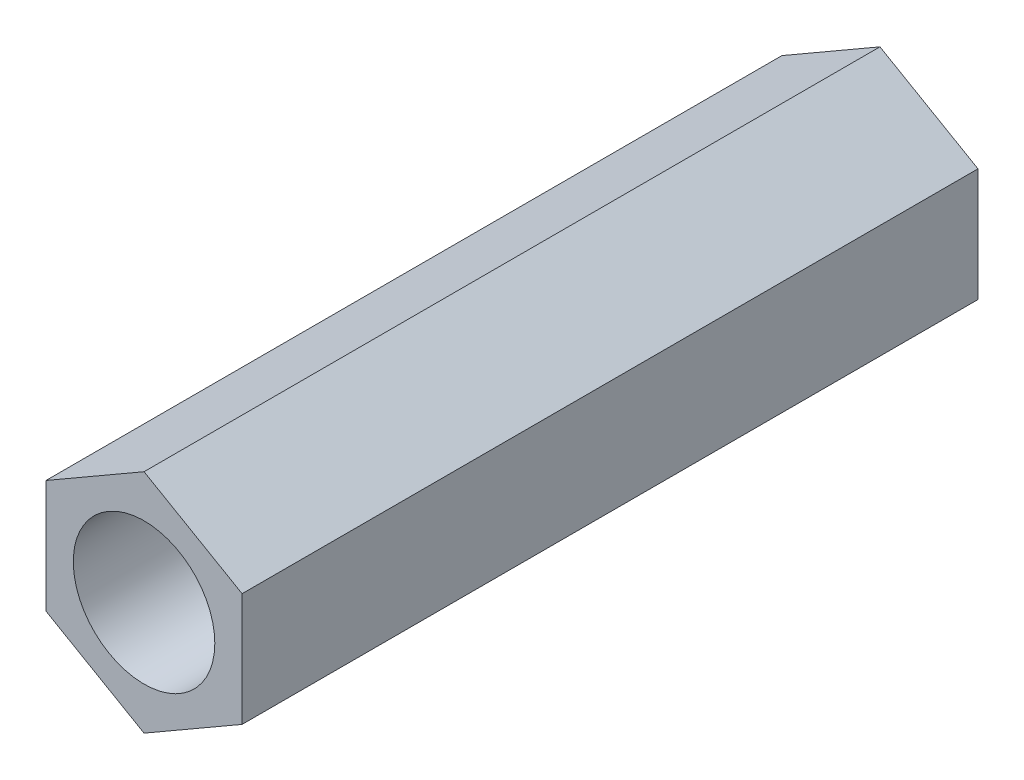
SolidWorks part; units mm, degrees
ref_plane "Front Plane" through (0, 0, 0) normal (0, 0, 1) x (1, 0, 0)
ref_plane "Top Plane" through (0, 0, 0) normal (0, 1, 0) x (1, 0, 0)
ref_plane "Right Plane" through (0, 0, 0) normal (1, 0, 0) x (0, 0, -1)
sketch "Sketch1" plane through (0, 0, 0) normal (0, 0, 1) x (1, 0, 0)
  line L0 (0, 108.4376) -> (0, -121.4916) construction
  line L1 (-136.8551, 0) -> (144.4002, 0) construction
  line L2 (0, 101.6) -> (87.9882, 50.8)
  line L3 (87.9882, 50.8) -> (87.9882, -50.8)
  line L4 (87.9882, -50.8) -> (0, -101.6)
  line L6 (-87.9882, -50.8) -> (0, -101.6)
  line L7 (-87.9882, 50.8) -> (-87.9882, -50.8)
  line L8 (0, 101.6) -> (-87.9882, 50.8)
  circle A1 centre (0, 0) radius 63.5
  point P2 (0, 73.429)
  dimension "D1" = 101.6
  dimension "D2" = 120
  dimension "D3" = 50.8
extrude "Boss-Extrude1" add sketch "Sketch1" along normal blind 660.4
